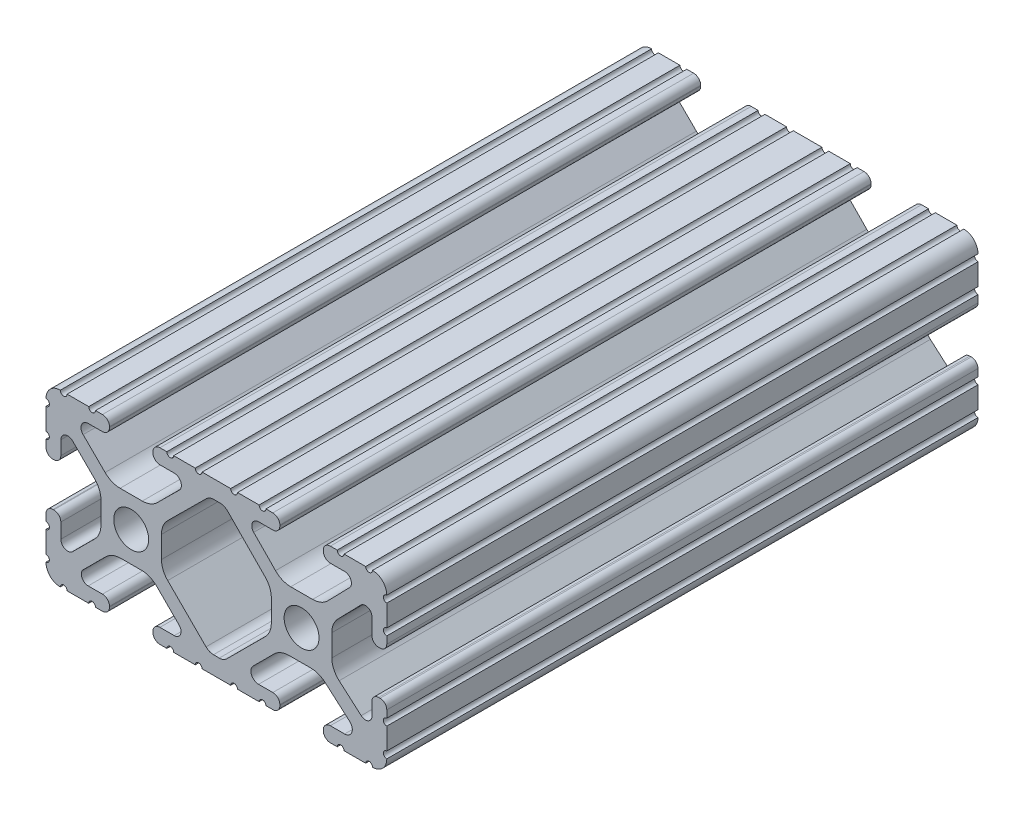
SolidWorks part; units mm, degrees
ref_plane "Front Plane" through (0, 0, 0) normal (0, 0, 1) x (1, 0, 0)
ref_plane "Top Plane" through (0, 0, 0) normal (0, 1, 0) x (1, 0, 0)
ref_plane "Right Plane" through (0, 0, 0) normal (1, 0, 0) x (0, 0, -1)
sketch "Sketch1" plane through (0, 0, 0) normal (0, 0, 1) x (1, 0, 0)
  line L0 (-7.2595, -3.8694) -> (-1.5457, -9.5728)
  line L1 (-8.1915, 1.6223) -> (-8.1915, -1.6223)
  line L2 (-1.504, 9.5765) -> (-7.252, 3.8768)
  line L3 (0.5515, 10.033) -> (-0.3952, 10.033)
  line L4 (7.2829, 3.8459) -> (1.6756, 9.5611)
  line L5 (8.1915, -1.6223) -> (8.1915, 1.6223)
  line L6 (1.5457, -9.5728) -> (7.2595, -3.8694)
  line L7 (-0.4332, -10.033) -> (0.4332, -10.033)
  line L8 (18.0171, 12.7) -> (16.9875, 12.7)
  line L9 (15.9385, 11.651) -> (15.9385, 11.5392)
  line L10 (16.9875, 10.4902) -> (19.1164, 10.4902)
  line L11 (19.8441, 8.7652) -> (16.619, 5.4551)
  line L12 (14.3449, 4.4958) -> (11.0833, 4.4958)
  line L13 (8.817, 5.4472) -> (5.5642, 8.7627)
  line L14 (6.2894, 10.4902) -> (8.4125, 10.4902)
  line L15 (9.4615, 11.5392) -> (9.4615, 11.651)
  line L16 (8.4125, 12.7) -> (7.3829, 12.7)
  line L17 (6.3669, 12.7) -> (3.1496, 12.7)
  line L18 (2.1336, 12.7) -> (-2.1336, 12.7)
  line L19 (-3.1496, 12.7) -> (-6.3669, 12.7)
  line L20 (-7.3829, 12.7) -> (-8.4125, 12.7)
  line L21 (-9.4615, 11.651) -> (-9.4615, 11.5392)
  line L22 (-8.4125, 10.4902) -> (-6.2836, 10.4902)
  line L23 (-5.5326, 8.6661) -> (-8.81, 5.4163)
  line L24 (-11.0455, 4.4958) -> (-14.3545, 4.4958)
  line L25 (-16.59, 5.4163) -> (-19.8674, 8.6661)
  line L26 (-19.1164, 10.4902) -> (-16.9875, 10.4902)
  line L27 (-15.9385, 11.5392) -> (-15.9385, 11.651)
  line L28 (-16.9875, 12.7) -> (-18.0171, 12.7)
  line L29 (-19.0331, 12.7) -> (-22.2504, 12.7)
  line L30 (-25.4, 9.5504) -> (-25.4, 6.3331)
  line L31 (-25.4, 5.3171) -> (-25.4, 4.2375)
  line L32 (-24.401, 3.2385) -> (-24.2392, 3.2385)
  line L33 (-23.1902, 4.2875) -> (-23.1902, 6.3347)
  line L34 (-21.434, 7.0665) -> (-18.148, 3.8082)
  line L35 (-17.2085, 1.5536) -> (-17.2085, -1.6952)
  line L36 (-18.1405, -3.9423) -> (-21.4316, -7.2274)
  line L37 (-23.1902, -6.498) -> (-23.1902, -4.2875)
  line L38 (-24.2392, -3.2385) -> (-24.351, -3.2385)
  line L39 (-25.4, -4.2875) -> (-25.4, -5.3171)
  line L40 (-25.4, -6.3331) -> (-25.4, -9.5504)
  line L41 (-22.2504, -12.7) -> (-19.0331, -12.7)
  line L42 (-18.0171, -12.7) -> (-16.9875, -12.7)
  line L43 (-15.9384, -11.651) -> (-15.9384, -11.5392)
  line L44 (-16.9875, -10.4902) -> (-19.1164, -10.4902)
  line L45 (-19.8341, -8.7551) -> (-16.4966, -5.4237)
  line L46 (-14.2536, -4.4958) -> (-11.1464, -4.4958)
  line L47 (-8.9034, -5.4237) -> (-5.5659, -8.7551)
  line L48 (-6.2836, -10.4902) -> (-8.4125, -10.4902)
  line L49 (-9.4616, -11.5392) -> (-9.4616, -11.651)
  line L50 (-8.4125, -12.7) -> (-7.3829, -12.7)
  line L51 (-6.3669, -12.7) -> (-3.1496, -12.7)
  line L52 (-2.1336, -12.7) -> (2.1336, -12.7)
  line L53 (3.1496, -12.7) -> (6.3669, -12.7)
  line L54 (7.3829, -12.7) -> (8.4125, -12.7)
  line L55 (9.4616, -11.651) -> (9.4616, -11.5392)
  line L56 (8.4125, -10.4902) -> (6.2894, -10.4902)
  line L57 (5.4807, -8.5353) -> (8.5979, -5.4237)
  line L58 (10.8409, -4.4958) -> (14.1026, -4.4958)
  line L59 (16.1879, -5.2766) -> (19.8682, -8.4822)
  line L60 (19.1164, -10.4902) -> (16.9875, -10.4902)
  line L61 (15.9384, -11.5392) -> (15.9384, -11.651)
  line L62 (16.9875, -12.7) -> (18.0171, -12.7)
  line L63 (19.0331, -12.7) -> (22.2504, -12.7)
  line L64 (25.4, -9.5504) -> (25.4, -6.3331)
  line L65 (25.4, -5.3171) -> (25.4, -4.2375)
  line L66 (24.401, -3.2385) -> (24.1892, -3.2385)
  line L67 (23.1902, -4.2375) -> (23.1902, -6.1559)
  line L68 (21.584, -6.8869) -> (18.2982, -4.025)
  line L69 (17.2085, -1.6308) -> (17.2085, 1.6308)
  line L70 (18.1094, 3.8465) -> (21.5263, 7.3534)
  line L71 (23.1902, 6.6769) -> (23.1902, 4.2375)
  line L72 (24.1892, 3.2385) -> (24.401, 3.2385)
  line L73 (25.4, 4.2375) -> (25.4, 5.3171)
  line L74 (25.4, 6.3332) -> (25.4, 9.5504)
  line L75 (22.2504, 12.7) -> (19.0331, 12.7)
  circle A0 centre (-12.7, 0) radius 2.6035
  circle A1 centre (12.7, 0) radius 2.6035
  arc A2 (-1.5457, -9.5728) -> (-0.4332, -10.033) centre (-0.4332, -8.4582) ccw
  arc A3 (-8.1915, -1.6223) -> (-7.2595, -3.8694) centre (-5.0165, -1.6223) ccw
  arc A4 (-7.252, 3.8768) -> (-8.1915, 1.6223) centre (-5.0165, 1.6223) ccw
  arc A5 (-0.3952, 10.033) -> (-1.504, 9.5765) centre (-0.3952, 8.4582) ccw
  arc A6 (1.6756, 9.5611) -> (0.5515, 10.033) centre (0.5515, 8.4582) ccw
  arc A7 (8.1915, 1.6223) -> (7.2829, 3.8459) centre (5.0165, 1.6223) ccw
  arc A8 (7.2595, -3.8694) -> (8.1915, -1.6223) centre (5.0165, -1.6223) ccw
  arc A9 (0.4332, -10.033) -> (1.5457, -9.5728) centre (0.4332, -8.4582) ccw
  arc A10 (18.0171, 12.7) -> (19.0331, 12.7) centre (18.5251, 12.7) ccw
  arc A11 (16.9875, 12.7) -> (15.9385, 11.651) centre (16.9875, 11.651) ccw
  arc A12 (15.9385, 11.5392) -> (16.9875, 10.4902) centre (16.9875, 11.5392) ccw
  arc A13 (19.8441, 8.7652) -> (19.1164, 10.4902) centre (19.1164, 9.4742) ccw
  arc A14 (14.3449, 4.4958) -> (16.619, 5.4551) centre (14.3449, 7.6708) ccw
  arc A15 (8.817, 5.4472) -> (11.0833, 4.4958) centre (11.0833, 7.6708) ccw
  arc A16 (6.2894, 10.4902) -> (5.5642, 8.7627) centre (6.2894, 9.4742) ccw
  arc A17 (8.4125, 10.4902) -> (9.4615, 11.5392) centre (8.4125, 11.5392) ccw
  arc A18 (9.4615, 11.651) -> (8.4125, 12.7) centre (8.4125, 11.651) ccw
  arc A19 (6.3669, 12.7) -> (7.3829, 12.7) centre (6.8749, 12.7) ccw
  arc A20 (2.1336, 12.7) -> (3.1496, 12.7) centre (2.6416, 12.7) ccw
  arc A21 (-3.1496, 12.7) -> (-2.1336, 12.7) centre (-2.6416, 12.7) ccw
  arc A22 (-7.3829, 12.7) -> (-6.3669, 12.7) centre (-6.8749, 12.7) ccw
  arc A23 (-8.4125, 12.7) -> (-9.4615, 11.651) centre (-8.4125, 11.651) ccw
  arc A24 (-9.4615, 11.5392) -> (-8.4125, 10.4902) centre (-8.4125, 11.5392) ccw
  arc A25 (-5.5326, 8.6661) -> (-6.2836, 10.4902) centre (-6.2836, 9.4235) ccw
  arc A26 (-11.0455, 4.4958) -> (-8.81, 5.4163) centre (-11.0455, 7.6708) ccw
  arc A27 (-16.59, 5.4163) -> (-14.3545, 4.4958) centre (-14.3545, 7.6708) ccw
  arc A28 (-19.1164, 10.4902) -> (-19.8674, 8.6661) centre (-19.1164, 9.4235) ccw
  arc A29 (-16.9875, 10.4902) -> (-15.9385, 11.5392) centre (-16.9875, 11.5392) ccw
  arc A30 (-15.9385, 11.651) -> (-16.9875, 12.7) centre (-16.9875, 11.651) ccw
  arc A31 (-19.0331, 12.7) -> (-18.0171, 12.7) centre (-18.5251, 12.7) ccw
  arc A32 (-23.2664, 12.6998) -> (-22.2504, 12.7) centre (-22.7584, 12.7) ccw
  arc A33 (-23.2664, 12.6998) -> (-25.3998, 10.5664) centre (-23.2918, 10.5918) ccw
  arc A34 (-25.4, 9.5504) -> (-25.3998, 10.5664) centre (-25.4, 10.0584) ccw
  arc A35 (-25.4, 5.3171) -> (-25.4, 6.3331) centre (-25.4, 5.8251) ccw
  arc A36 (-25.4, 4.2375) -> (-24.401, 3.2385) centre (-24.401, 4.2375) ccw
  arc A37 (-24.2392, 3.2385) -> (-23.1902, 4.2875) centre (-24.2392, 4.2875) ccw
  arc A38 (-21.434, 7.0665) -> (-23.1902, 6.3347) centre (-22.1596, 6.3347) ccw
  arc A39 (-17.2085, 1.5536) -> (-18.148, 3.8082) centre (-20.3835, 1.5536) ccw
  arc A40 (-18.1405, -3.9423) -> (-17.2085, -1.6952) centre (-20.3835, -1.6952) ccw
  arc A41 (-23.1902, -6.498) -> (-21.4316, -7.2274) centre (-22.1596, -6.498) ccw
  arc A42 (-23.1902, -4.2875) -> (-24.2392, -3.2385) centre (-24.2392, -4.2875) ccw
  arc A43 (-24.351, -3.2385) -> (-25.4, -4.2875) centre (-24.351, -4.2875) ccw
  arc A44 (-25.4, -6.3331) -> (-25.4, -5.3171) centre (-25.4, -5.8251) ccw
  arc A45 (-25.3998, -10.5664) -> (-25.4, -9.5504) centre (-25.4, -10.0584) ccw
  arc A46 (-25.3998, -10.5664) -> (-23.2664, -12.6998) centre (-23.2918, -10.5918) ccw
  arc A47 (-22.2504, -12.7) -> (-23.2664, -12.6998) centre (-22.7584, -12.7) ccw
  arc A48 (-18.0171, -12.7) -> (-19.0331, -12.7) centre (-18.5251, -12.7) ccw
  arc A49 (-16.9875, -12.7) -> (-15.9384, -11.651) centre (-16.9875, -11.651) ccw
  arc A50 (-15.9384, -11.5392) -> (-16.9875, -10.4902) centre (-16.9875, -11.5392) ccw
  arc A51 (-19.8341, -8.7551) -> (-19.1164, -10.4902) centre (-19.1164, -9.4742) ccw
  arc A52 (-14.2536, -4.4958) -> (-16.4966, -5.4237) centre (-14.2536, -7.6708) ccw
  arc A53 (-8.9034, -5.4237) -> (-11.1464, -4.4958) centre (-11.1464, -7.6708) ccw
  arc A54 (-6.2836, -10.4902) -> (-5.5659, -8.7551) centre (-6.2836, -9.4742) ccw
  arc A55 (-8.4125, -10.4902) -> (-9.4616, -11.5392) centre (-8.4125, -11.5392) ccw
  arc A56 (-9.4616, -11.651) -> (-8.4125, -12.7) centre (-8.4125, -11.651) ccw
  arc A57 (-6.3669, -12.7) -> (-7.3829, -12.7) centre (-6.8749, -12.7) ccw
  arc A58 (-2.1336, -12.7) -> (-3.1496, -12.7) centre (-2.6416, -12.7) ccw
  arc A59 (3.1496, -12.7) -> (2.1336, -12.7) centre (2.6416, -12.7) ccw
  arc A60 (7.3829, -12.7) -> (6.3669, -12.7) centre (6.8749, -12.7) ccw
  arc A61 (8.4125, -12.7) -> (9.4616, -11.651) centre (8.4125, -11.651) ccw
  arc A62 (9.4616, -11.5392) -> (8.4125, -10.4902) centre (8.4125, -11.5392) ccw
  arc A63 (5.4807, -8.5353) -> (6.2894, -10.4902) centre (6.2894, -9.3455) ccw
  arc A64 (10.8409, -4.4958) -> (8.5979, -5.4237) centre (10.8409, -7.6708) ccw
  arc A65 (16.1879, -5.2766) -> (14.1026, -4.4958) centre (14.1026, -7.6708) ccw
  arc A66 (19.1164, -10.4902) -> (19.8682, -8.4822) centre (19.1164, -9.3455) ccw
  arc A67 (16.9875, -10.4902) -> (15.9384, -11.5392) centre (16.9875, -11.5392) ccw
  arc A68 (15.9384, -11.651) -> (16.9875, -12.7) centre (16.9875, -11.651) ccw
  arc A69 (19.0331, -12.7) -> (18.0171, -12.7) centre (18.5251, -12.7) ccw
  arc A70 (23.2664, -12.6998) -> (22.2504, -12.7) centre (22.7584, -12.7) ccw
  arc A71 (23.2664, -12.6998) -> (25.3998, -10.5664) centre (23.2918, -10.5918) ccw
  arc A72 (25.4, -9.5504) -> (25.3998, -10.5664) centre (25.4, -10.0584) ccw
  arc A73 (25.4, -5.3171) -> (25.4, -6.3331) centre (25.4, -5.8251) ccw
  arc A74 (25.4, -4.2375) -> (24.401, -3.2385) centre (24.401, -4.2375) ccw
  arc A75 (24.1892, -3.2385) -> (23.1902, -4.2375) centre (24.1892, -4.2375) ccw
  arc A76 (21.584, -6.8869) -> (23.1902, -6.1559) centre (22.2207, -6.1559) ccw
  arc A77 (17.2085, -1.6308) -> (18.2982, -4.025) centre (20.3835, -1.6308) ccw
  arc A78 (18.1094, 3.8465) -> (17.2085, 1.6308) centre (20.3835, 1.6308) ccw
  arc A79 (23.1902, 6.6769) -> (21.5263, 7.3534) centre (22.2207, 6.6769) ccw
  arc A80 (23.1902, 4.2375) -> (24.1892, 3.2385) centre (24.1892, 4.2375) ccw
  arc A81 (24.401, 3.2385) -> (25.4, 4.2375) centre (24.401, 4.2375) ccw
  arc A82 (25.4, 6.3332) -> (25.4, 5.3171) centre (25.4, 5.8251) ccw
  arc A83 (25.3998, 10.5664) -> (25.4, 9.5504) centre (25.4, 10.0584) ccw
  arc A84 (25.3998, 10.5664) -> (23.2664, 12.6998) centre (23.2918, 10.5918) ccw
  arc A85 (22.2504, 12.7) -> (23.2664, 12.6998) centre (22.7584, 12.7) ccw
  point P248 (0, 10.033)
extrude "Boss-Extrude1" add sketch "Sketch1" along normal blind 88.138
